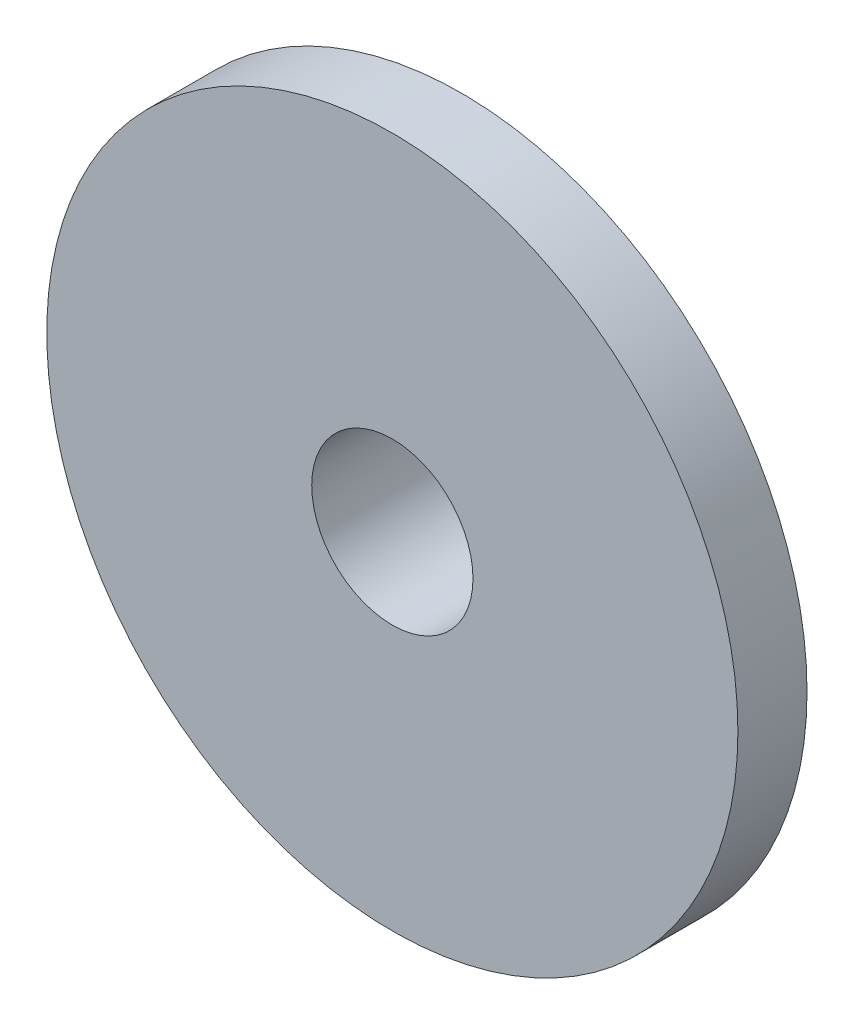
SolidWorks part; units mm, degrees
ref_plane "Front Plane" through (0, 0, 0) normal (0, 0, 1) x (1, 0, 0)
ref_plane "Top Plane" through (0, 0, 0) normal (0, 1, 0) x (1, 0, 0)
ref_plane "Right Plane" through (0, 0, 0) normal (1, 0, 0) x (0, 0, -1)
sketch "Sketch1" plane through (0, 0, 0) normal (0, 0, 1) x (1, 0, 0)
  circle A0 centre (-0.8602, 39.9907) radius 15
  circle A1 centre (-0.8602, 39.9907) radius 4
  dimension "D1" = 30
  dimension "D2" = 8
extrude "Boss-Extrude1" add sketch "Sketch1" along normal blind 3
sketch "Sketch2" plane through (0, 0, 0) normal (0, 0, -1) x (-1, 0, 0)
  circle A0 centre (0.8602, 39.9907) radius 4
  circle A1 centre (0.8602, 39.9907) radius 3.5
  dimension "D1" = 0.5
  dimension "D2" = 8
extrude "Boss-Extrude2" add sketch "Sketch2" along normal blind 5 separate body
sketch "Sketch4" plane through (0, 0, 0) normal (0, 0, 1) x (1, 0, 0)
  circle A0 centre (-0.8602, 39.9907) radius 3.5
  circle A1 centre (-0.8602, 39.9907) radius 4
  circle A2 centre (-0.8602, 39.9907) radius 4
  dimension "D1" = 0
extrude "Boss-Extrude4" add sketch "Sketch4" along normal blind 3
